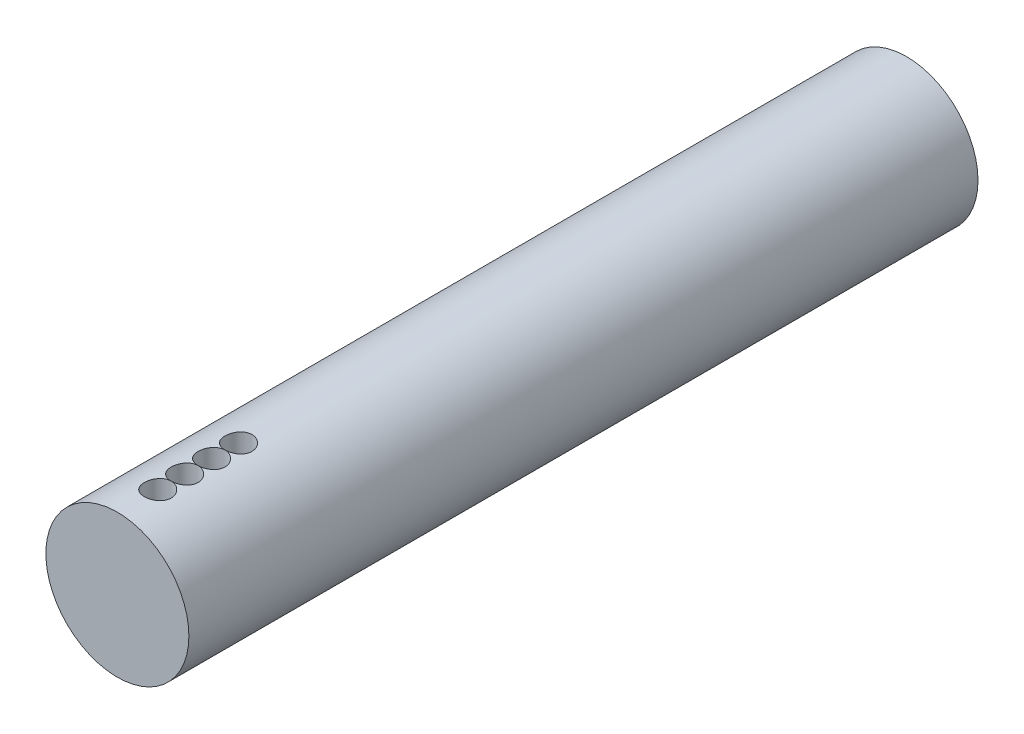
SolidWorks part; units mm, degrees
material "Alumina"
ref_plane "Front Plane" through (0, 0, 0) normal (0, 0, 1) x (1, 0, 0)
ref_plane "Top Plane" through (0, 0, 0) normal (0, 1, 0) x (1, 0, 0)
ref_plane "Right Plane" through (0, 0, 0) normal (1, 0, 0) x (0, 0, -1)
sketch "Sketch1" plane through (0, 0, 0) normal (0, 0, 1) x (1, 0, 0)
  circle A0 centre (0, 0) radius 7.975
  dimension "D1" = 15.95
extrude "Boss-Extrude1" add sketch "Sketch1" along normal mid plane 88
sketch "Sketch2" plane through (0, 0, 0) normal (0, 1, 0) x (1, 0, 0)
  line L0 (7.975, 44) -> (7.975, -44)
  line L1 (-7.975, -41) -> (7.975, -41) construction
  line L2 (-7.975, 44) -> (-7.975, -44) construction
  line L3 (7.975, -44) -> (7.975, 44) construction
  line L4 (7.975, 44) -> (7.975, -44) construction
  line L6 (7.975, -44) -> (-7.975, -44)
  line L7 (7.975, -44) -> (-7.975, -44) construction
  line L8 (-7.975, -44) -> (-7.975, 44)
  line L9 (-7.975, -44) -> (-7.975, 44) construction
  line L10 (-7.975, 44) -> (7.975, 44)
  line L11 (-7.975, 44) -> (7.975, 44) construction
  circle A1 centre (0, -39.5) radius 1.5
  dimension "D1" = 3
  dimension "D2" = 3
extrude "Cut-Extrude1" cut sketch "Sketch2" against normal through all both and the other way through all
pattern_linear "LPattern1-Planet1" [suppressed] count 4 spacing 3.001
pattern_linear "LPattern3-Planet2" count 4 spacing 3.001 along (0, 0, -1) of "Cut-Extrude1"
equation "\"shaft_diameter\"= 15.95"
equation "\"key_diameter\"=3"
equation "\"key_number\"= 4"
equation "\"key_distance_front\"=3"
equation "\"key_distance_back\"= 73"
equation "\"key_depth\"= 5"
equation "\"D1@Sketch1\"=\"shaft_diameter\""
equation "\"D1@Boss-Extrude1\"=\"key_distance_front\" + (\"key_number\" * \"key_diameter\") + \"key_distance_back\""
equation "\"D1@Sketch2\"=\"key_diameter\""
equation "\"key_height\"=1.5"
equation "\"D1@LPattern3-Planet2\" = \"key_number\""
equation "\"D3@LPattern3-Planet2\" = \"key_diameter\" + 0.001"
equation "\"D3@LPattern1-Planet1\"=\"key_diameter\" + 0.001"
equation "\"D1@LPattern1-Planet1\"=\"key_number\""
equation "\"D2@Sketch2\"=\"key_distance_front\""
